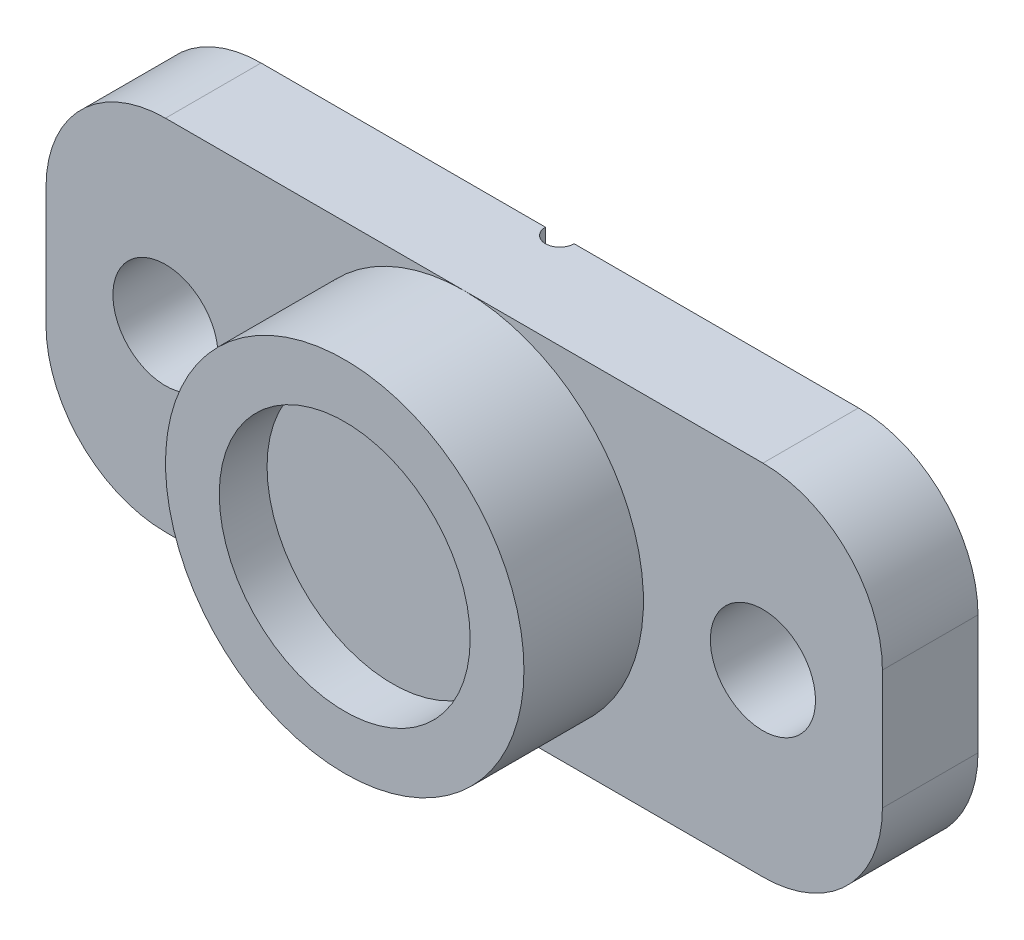
SolidWorks part; units mm, degrees
ref_plane "Alzado" through (0, 0, 0) normal (0, 0, 1) x (1, 0, 0)
ref_plane "Planta" through (0, 0, 0) normal (0, 1, 0) x (1, 0, 0)
ref_plane "Vista lateral" through (0, 0, 0) normal (1, 0, 0) x (0, 0, -1)
sketch "Croquis1" plane through (0, 0, 0) normal (0, 0, 1) x (1, 0, 0)
  line L0 (0, 0) -> (0, 15)
  line L1 (0, 15) -> (35, 15)
  line L2 (35, 15) -> (35, 0)
  line L3 (35, 0) -> (0, 0)
  circle A0 centre (5, 7.5) radius 2.2
  circle A1 centre (30, 7.5) radius 2.2
extrude "Saliente-Extruir1" add sketch "Croquis1" along normal blind 4
sketch "Croquis2" plane through (0, 0, 4) normal (0, 0, 1) x (1, 0, 0)
  circle A0 centre (17.5, 7.5) radius 5.25
  circle A1 centre (17.5, 7.5) radius 7.5
extrude "Saliente-Extruir2" add sketch "Croquis2" along normal blind 5
fillet "Redondeo1" radius 5 4 edges at (0, 0, 2) (0, 15, 2) (35, 0, 2) (35, 15, 2)
sketch "Croquis3" plane through (0, 15, 0) normal (0, 1, 0) x (1, 0, 0)
  line L0 (30, 0) -> (5, 0) construction
  circle A0 centre (17.5, 0) radius 0.6
extrude "Cortar-Extruir1" cut sketch "Croquis3" against normal blind 32
sketch "Croquis4" plane through (0, 0, 4) normal (0, 0, 1) x (1, 0, 0)
  circle A0 centre (17.5, 7.5) radius 5.25
extrude "Saliente-Extruir3" add sketch "Croquis4" along normal blind 3
